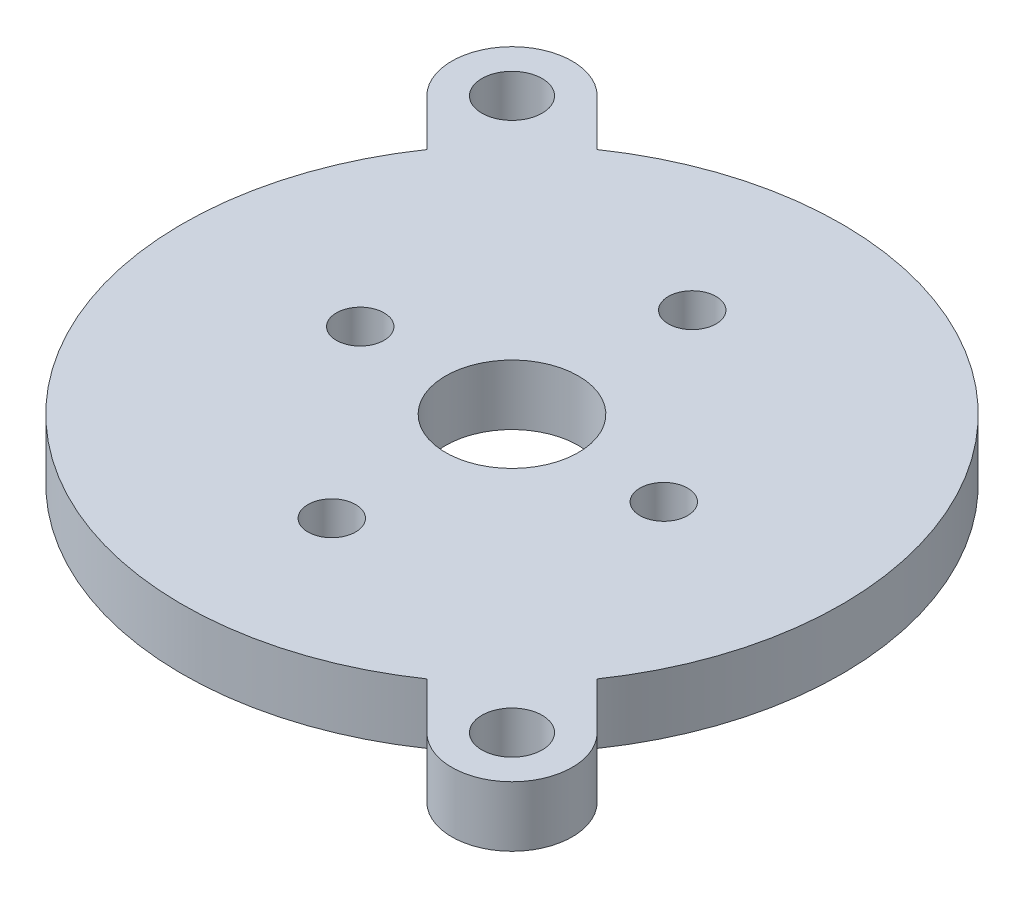
SolidWorks part; units mm, degrees
ref_plane "Front Plane" through (0, 0, 0) normal (0, 0, 1) x (1, 0, 0)
ref_plane "Top Plane" through (0, 0, 0) normal (0, 1, 0) x (1, 0, 0)
ref_plane "Right Plane" through (0, 0, 0) normal (1, 0, 0) x (0, 0, -1)
sketch "Sketch1" plane through (0, 0, 0) normal (0, 0, 1) x (1, 0, 0)
  line L0 (0, 0) -> (0, 25451.8246) construction
  line L1 (17.379, 3.175) -> (17.379, 0)
  line L2 (17.379, 0) -> (3.5, 0)
  line L3 (3.5, 0) -> (3.5, 3.175)
  line L4 (3.5, 3.175) -> (14.204, 3.175)
  line L7 (14.204, 3.175) -> (17.379, 3.175)
  dimension "D2" = 3.175
  dimension "D3" = 3.5
revolve "Revolve1" add sketch "Sketch1" angle 360 about L0
sketch "Sketch3" plane through (0, 3.175, 0) normal (0, 1, 0) x (1, 0, 0)
  line L0 (8, 0) -> (-8, 0) construction
  line L1 (0, 9.5) -> (0, -9.5) construction
  circle A0 centre (0, -9.5) radius 1.2573
  circle A1 centre (-8, 0) radius 1.2573
  circle A2 centre (0, 9.5) radius 1.2573
  circle A3 centre (8, 0) radius 1.2573
  point P4 (0, 0)
  point P5 (0, 0)
  dimension "D3" = 2.5146
  dimension "D1" = 19
  dimension "D2" = 16
extrude "Cut-Extrude1" cut sketch "Sketch3" against normal through all
sketch "Sketch4" plane through (0, 0, 0) normal (0, 1, 0) x (1, 0, 0)
  line L0 (707.1068, -707.1068) -> (0, 0) construction
  line L1 (1000, 0) -> (0, 0) construction
  line L2 (16.7789, -12.2888) -> (14.3271, -9.8369)
  line L3 (12.2888, -16.7789) -> (9.8369, -14.3271)
  line L4 (704.8617, -709.3518) -> (-35357.5841, 35353.094) construction
  line L5 (709.3518, -704.8617) -> (-35353.094, 35357.5841) construction
  line L6 (-9.8369, 14.3271) -> (-12.2888, 16.7789)
  line L7 (-14.3271, 9.8369) -> (-16.7789, 12.2888)
  line L8 (-12.2888, 12.2888) -> (-35355.3391, 35355.3391) construction
  line L9 (707.1068, -707.1068) -> (-35355.3391, 35355.3391) construction
  circle A0 centre (-14.5339, 14.5339) radius 3.175
  circle A1 centre (0, 0) radius 17.379 construction
  circle A2 centre (14.5339, -14.5339) radius 3.175
  circle A3 centre (-14.5339, 14.5339) radius 1.5875
  circle A4 centre (14.5339, -14.5339) radius 1.5875
  arc A5 (9.8369, -14.3271) -> (14.3271, -9.8369) centre (0, 0) ccw
  arc A6 (-9.8369, 14.3271) -> (-14.3271, 9.8369) centre (0, 0) ccw
  dimension "D4" = 3.175
  dimension "D1" = 45
  dimension "D2" = 3.175
  dimension "D3" = 3.175
extrude "Boss-Extrude1" add sketch "Sketch4" along normal blind 3.175 contours A0 A3 | A6 L6 A0 | A6 A0 L7 | A2 A4 | A5 L3 A2 | A5 A2 L2
sketch "Sketch5" plane through (0, 3.175, 0) normal (0, 1, 0) x (1, 0, 0)
  arc A0 (14.3271, -9.8369) -> (-9.8369, 14.3271) centre (0, 0) ccw construction
  arc A1 (-14.3271, 9.8369) -> (9.8369, -14.3271) centre (0, 0) ccw construction
  circle A2 centre (8, 0) radius 1.2573 construction
  circle A3 centre (0, 9.5) radius 1.2573 construction
  circle A4 centre (-8, 0) radius 1.2573 construction
  circle A5 centre (0, -9.5) radius 1.2573 construction
  circle A6 centre (0, 0) radius 3.5 construction
  arc A7 (14.3271, -9.8369) -> (-9.8369, 14.3271) centre (0, 0) ccw
  arc A8 (-14.3271, 9.8369) -> (9.8369, -14.3271) centre (0, 0) ccw
  circle A9 centre (8, 0) radius 1.2573
  circle A10 centre (0, 9.5) radius 1.2573
  circle A11 centre (-8, 0) radius 1.2573
  circle A12 centre (0, -9.5) radius 1.2573
  circle A13 centre (0, 0) radius 3.5
  circle A14 centre (-8, 0) radius 2.75
  circle A15 centre (0, 9.5) radius 2.75
  circle A16 centre (8, 0) radius 2.75
  circle A17 centre (0, -9.5) radius 2.75
  dimension "D1" = 5.5
